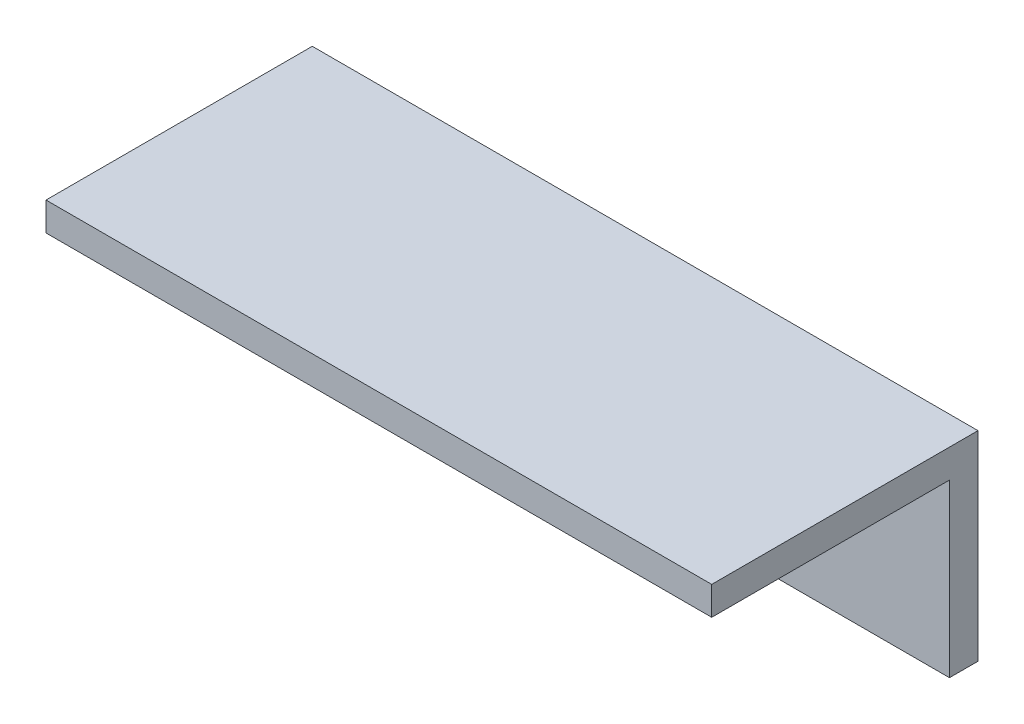
SolidWorks part; units mm, degrees
material "Maple"
ref_plane "Front Plane" through (0, 0, 0) normal (0, 0, 1) x (1, 0, 0)
ref_plane "Top Plane" through (0, 0, 0) normal (0, 1, 0) x (1, 0, 0)
ref_plane "Right Plane" through (0, 0, 0) normal (1, 0, 0) x (0, 0, -1)
sketch "Sketch1" plane through (0, 0, 0) normal (0, 1, 0) x (1, 0, 0)
  line L1 (0, 0) -> (350, 0)
  line L2 (0, 0) -> (0, -60)
  line L3 (0, -60) -> (350, -60)
  line L4 (350, 0) -> (350, -60)
  dimension "D1" = 350
  dimension "D2" = 60
extrude "Boss-Extrude1" add sketch "Sketch1" along normal blind 15
sketch "Sketch3" plane through (0, 0, 0) normal (0, 0, -1) x (-1, 0, 0)
  line L1 (-350, 15) -> (0, 15)
  line L2 (-350, 15) -> (-350, 0)
  line L3 (-350, 0) -> (0, 0)
  line L4 (0, 15) -> (0, 0)
extrude "Boss-Extrude4" add sketch "Sketch3" along normal blind 80
sketch "Sketch5" plane through (0, 0, 0) normal (0, -1, 0) x (1, 0, 0)
  line L0 (0, -80) -> (0, 60) construction
  line L1 (0, -65) -> (350, -65)
  line L2 (0, -65) -> (0, -80)
  line L3 (0, -80) -> (350, -80)
  line L4 (350, -65) -> (350, -80)
  dimension "D1" = 15
extrude "Boss-Extrude5" add sketch "Sketch5" along normal blind 90
